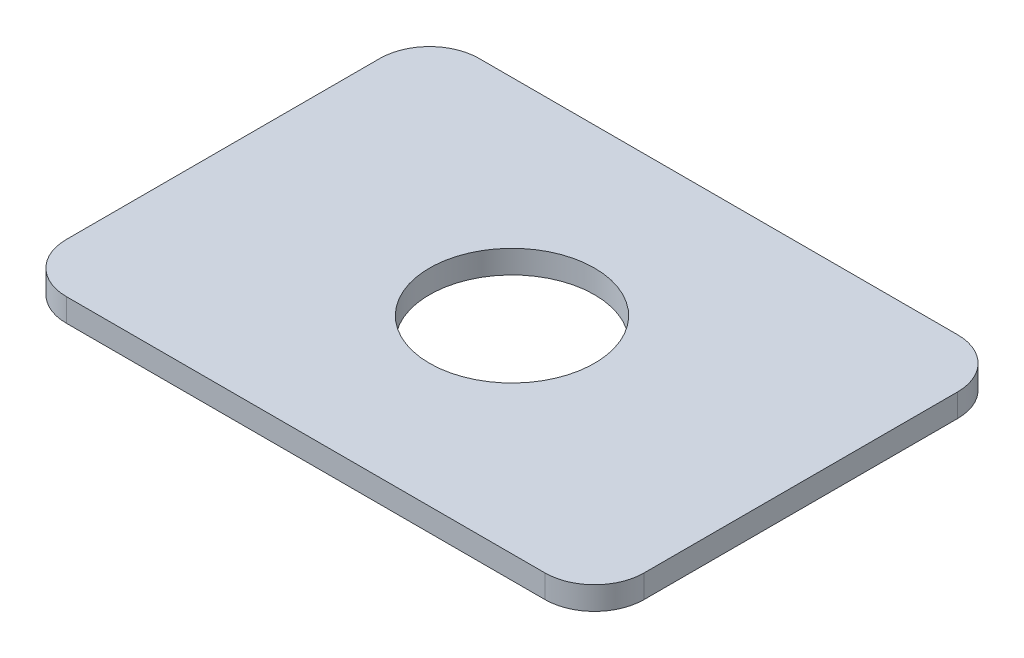
SolidWorks part; units mm, degrees
ref_plane "Front Plane" through (0, 0, 0) normal (0, 0, 1) x (1, 0, 0)
ref_plane "Top Plane" through (0, 0, 0) normal (0, 1, 0) x (1, 0, 0)
ref_plane "Right Plane" through (0, 0, 0) normal (1, 0, 0) x (0, 0, -1)
sketch "Sketch2" plane through (0, 0, 0) normal (0, 1, 0) x (1, 0, 0)
  line L1 (-17.5, -12.5) -> (17.5, -12.5)
  line L2 (-17.5, -12.5) -> (-17.5, 12.5)
  line L3 (-17.5, 12.5) -> (17.5, 12.5)
  line L4 (17.5, -12.5) -> (17.5, 12.5)
  line L5 (-17.5, -12.5) -> (17.5, 12.5) construction
  line L6 (-17.5, 12.5) -> (17.5, -12.5) construction
  point P0 (0, 0)
  dimension "D1" = 35
  dimension "D2" = 25
extrude "Boss-Extrude1" add sketch "Sketch2" along normal blind 1.4
fillet "Fillet1" radius 3 4 edges at (-17.5, 0.7, -12.5) (-17.5, 0.7, 12.5) (17.5, 0.7, -12.5) (17.5, 0.7, 12.5)
sketch "Sketch3" plane through (0, 1.4, 0) normal (0, 1, 0) x (1, 0, 0)
  circle A0 centre (0, 0) radius 5
  dimension "D1" = 10
extrude "Cut-Extrude1" cut sketch "Sketch3" against normal through all
